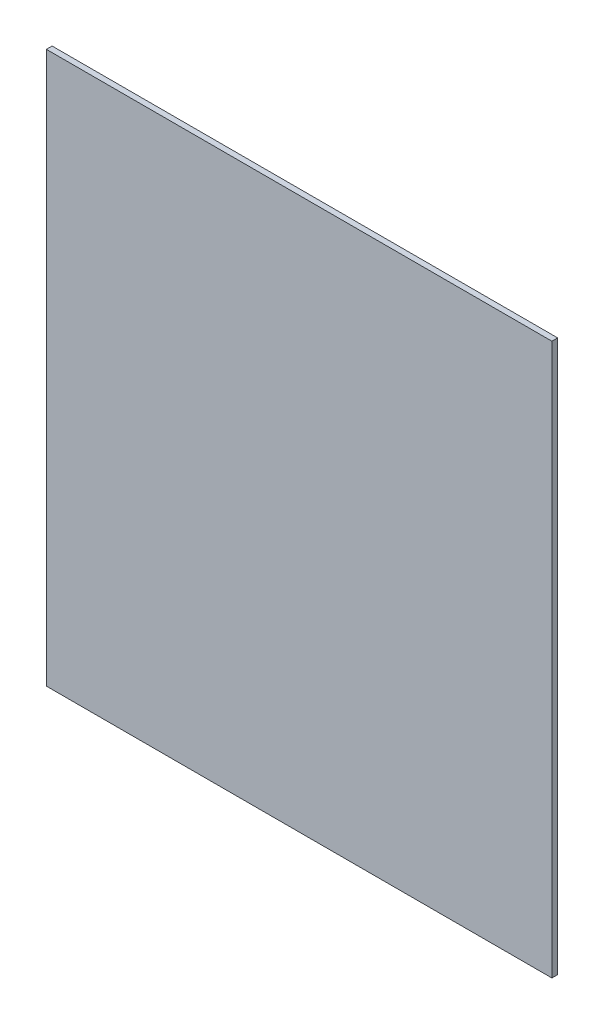
SolidWorks part; units mm, degrees
material "Copper"
ref_plane "Front Plane" through (0, 0, 0) normal (0, 0, 1) x (1, 0, 0)
ref_plane "Top Plane" through (0, 0, 0) normal (0, 1, 0) x (1, 0, 0)
ref_plane "Right Plane" through (0, 0, 0) normal (1, 0, 0) x (0, 0, -1)
sketch "Sketch1" plane through (0, 0, 0) normal (0, 0, 1) x (1, 0, 0)
  line L1 (0, 0) -> (-279.4, 0)
  line L2 (0, 0) -> (0, -304.8)
  line L3 (0, -304.8) -> (-279.4, -304.8)
  line L4 (-279.4, 0) -> (-279.4, -304.8)
  dimension "D1" = 304.8
  dimension "D2" = 279.4
extrude "Boss-Extrude1" add sketch "Sketch1" along normal blind 3.175
